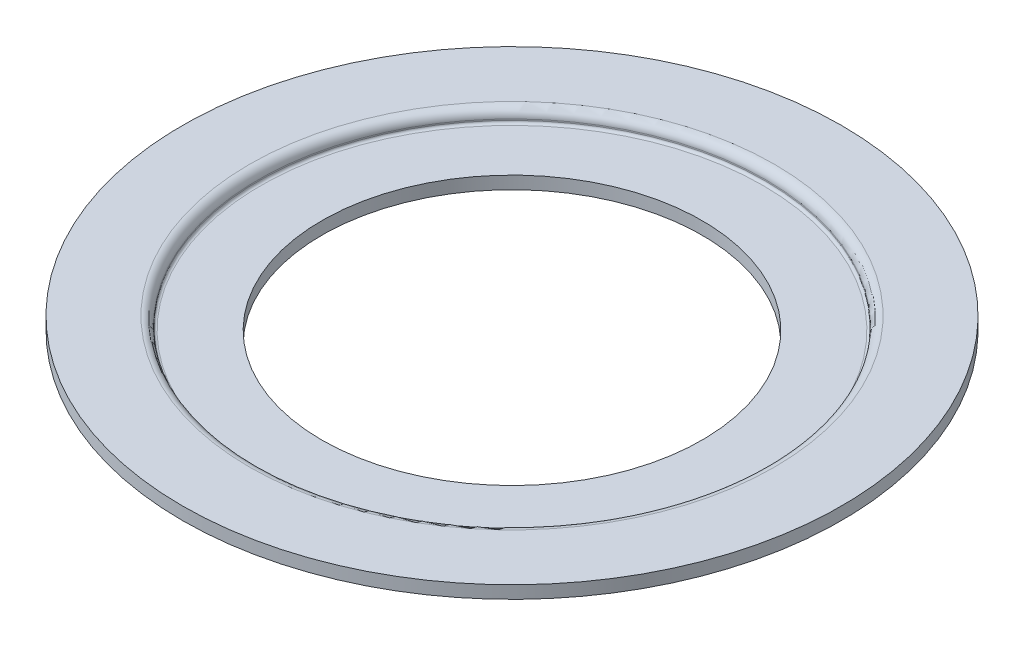
SolidWorks part; units mm, degrees
ref_plane "Plan1" through (0, 0, 0) normal (0, 0, 1) x (1, 0, 0)
ref_plane "Plan2" through (0, 0, 0) normal (0, 1, 0) x (1, 0, 0)
ref_plane "Plan3" through (0, 0, 0) normal (1, 0, 0) x (0, 0, -1)
sketch "Esquisse1" plane through (0, 0, 0) normal (0, 0, 1) x (1, 0, 0)
  line L0 (0, 0) -> (0, -10) construction
  line L1 (-26, 1) -> (-20, 1)
  line L2 (-20, 1) -> (-20, 0)
  line L3 (-20, 0) -> (-15, 0)
  dimension "D1" = 15
  dimension "D2" = 20
  dimension "D3" = 26
  dimension "D4" = 1
revolve "Base-Révol.-Mince" add sketch "Esquisse1" angle 360 about L0
fillet "Congé1" radius 0.7
fillet "Congé2" radius 0.2
